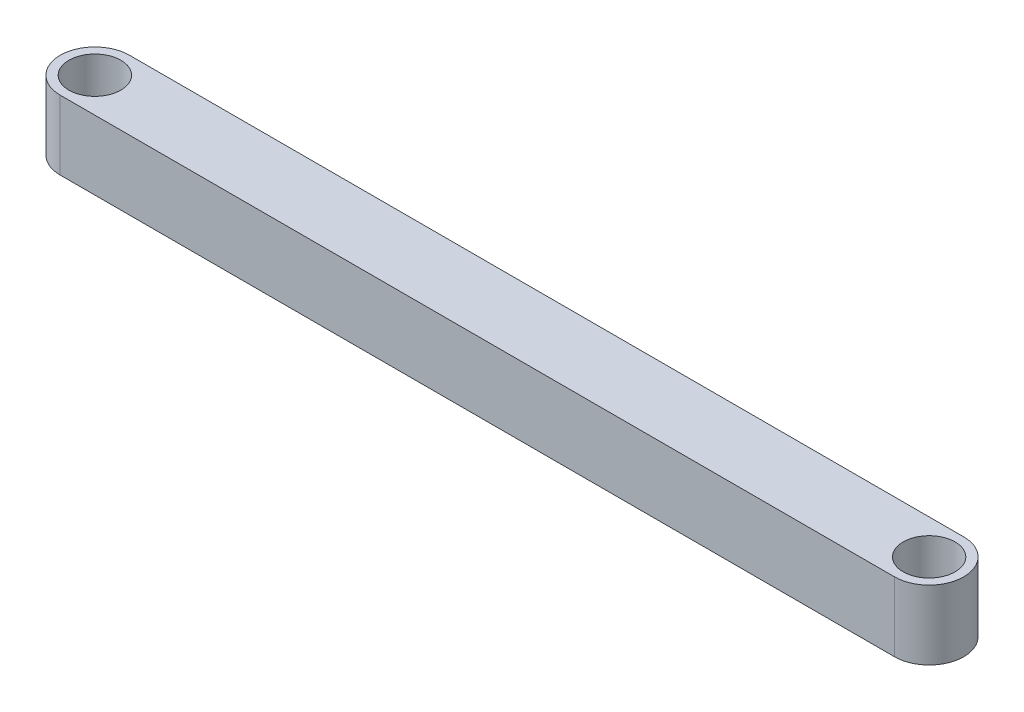
SolidWorks part; units mm, degrees
material "自定义塑料"
ref_plane "前视基准面" through (0, 0, 0) normal (0, 0, 1) x (1, 0, 0)
ref_plane "上视基准面" through (0, 0, 0) normal (0, 1, 0) x (1, 0, 0)
ref_plane "右视基准面" through (0, 0, 0) normal (1, 0, 0) x (0, 0, -1)
sketch "草图1" plane through (0, 0, 0) normal (0, 1, 0) x (1, 0, 0)
  line L0 (0, 0) -> (482, 0) construction
  line L1 (0, 20) -> (482, 20)
  line L2 (0, -20) -> (482, -20)
  arc A0 (0, 20) -> (0, -20) centre (0, 0) ccw
  arc A1 (482, -20) -> (482, 20) centre (482, 0) ccw
  circle A2 centre (0, 0) radius 15
  circle A3 centre (482, 0) radius 15
  point P3 (241, 0)
extrude "凸台-拉伸1" add sketch "草图1" along normal blind 40 contours A3 | A2 | L1 A1 L2 A0
